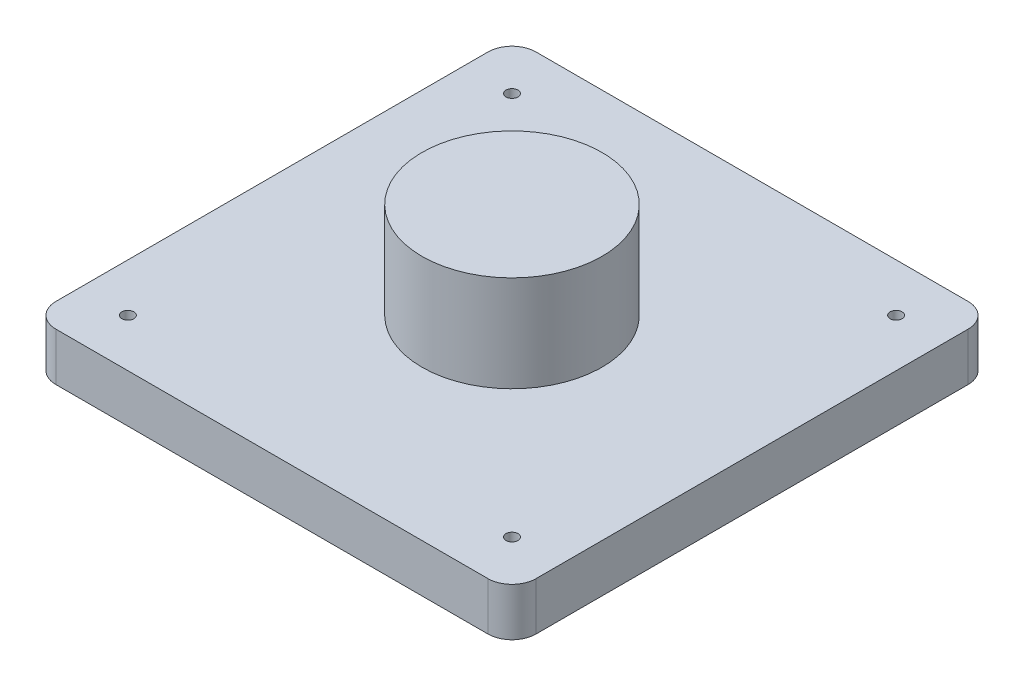
SolidWorks part; units mm, degrees
ref_plane "Front Plane" through (0, 0, 0) normal (0, 0, 1) x (1, 0, 0)
ref_plane "Top Plane" through (0, 0, 0) normal (0, 1, 0) x (1, 0, 0)
ref_plane "Right Plane" through (0, 0, 0) normal (1, 0, 0) x (0, 0, -1)
sketch "Sketch1" plane through (0, 0, 0) normal (0, 1, 0) x (1, 0, 0)
  line L1 (-90, -100) -> (90, -100)
  line L2 (-100, -90) -> (-100, 90)
  line L3 (-90, 100) -> (90, 100)
  line L4 (100, -90) -> (100, 90)
  arc A1 (-90, -100) -> (-100, -90) centre (-90, -90) cw
  arc A2 (90, -100) -> (100, -90) centre (90, -90) ccw
  arc A3 (90, 100) -> (100, 90) centre (90, 90) cw
  arc A4 (-100, 90) -> (-90, 100) centre (-90, 90) cw
  dimension "D1" = 10
  dimension "D2" = 100
  dimension "D3" = 200
  dimension "D4" = 200
  dimension "D5" = 100
extrude "Boss-Extrude1" add sketch "Sketch1" along normal blind 20
sketch "Sketch2" plane through (0, 20, 0) normal (0, 1, 0) x (1, 0, 0)
  circle A0 centre (0, 0) radius 37.5
  dimension "D1" = 75
extrude "Boss-Extrude2" add sketch "Sketch2" along normal blind 40 contours A0
sketch "Sketch3" plane through (0, 20, 0) normal (0, 1, 0) x (1, 0, 0)
  line L0 (-100, 90) -> (-100, -90) construction
  line L1 (90, 100) -> (-90, 100) construction
  line L2 (-90, -100) -> (90, -100) construction
  line L3 (100, -90) -> (100, 90) construction
  circle A0 centre (-80, 80) radius 2.5
  circle A1 centre (80, 80) radius 2.5
  circle A2 centre (80, -80) radius 2.5
  circle A3 centre (-80, -80) radius 2.5
  point P8 (0, 0)
  point P10 (0, 0)
  point P11 (0, 0)
  point P12 (0, 0)
  point P13 (0, 0)
  point P14 (0, 0)
  point P15 (0, 0)
  dimension "D1" = 5
  dimension "D2" = 20
  dimension "D3" = 20
  dimension "D4" = 20
  dimension "D5" = 20
extrude "Cut-Extrude1" cut sketch "Sketch3" against normal up to next
